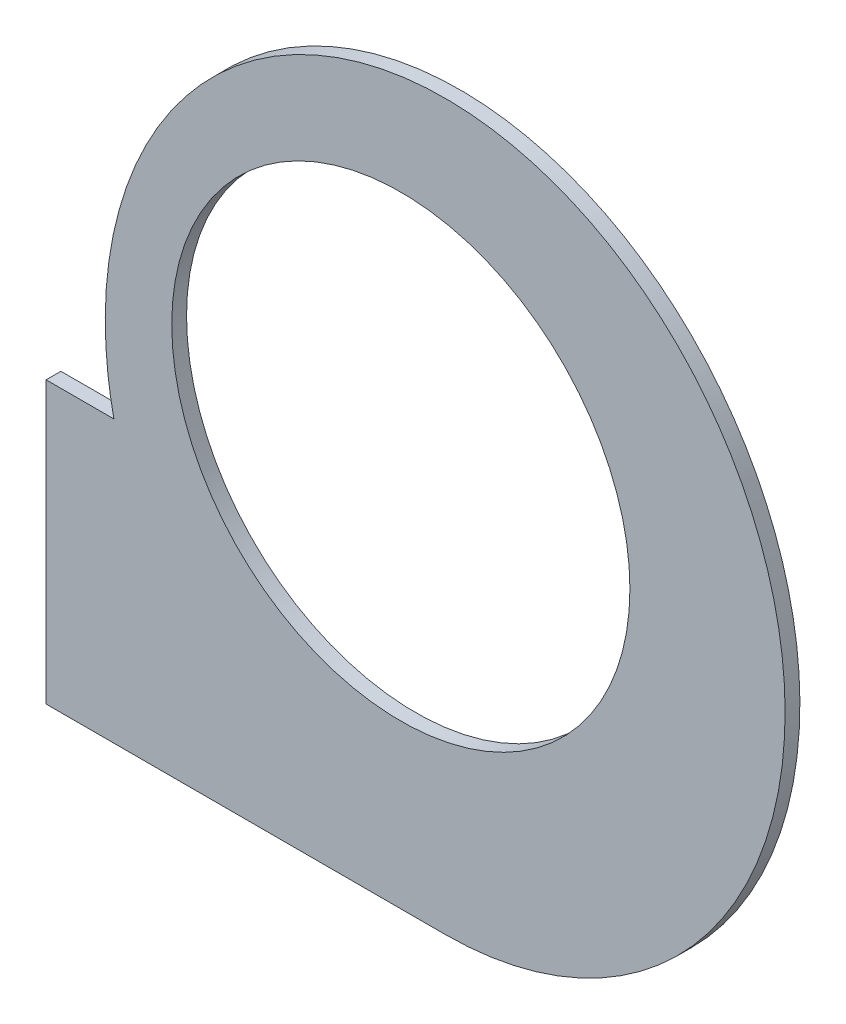
SolidWorks part; units mm, degrees
ref_plane "Plano frontal" through (0, 0, 0) normal (0, 0, 1) x (1, 0, 0)
ref_plane "Plano superior" through (0, 0, 0) normal (0, 1, 0) x (1, 0, 0)
ref_plane "Plano direito" through (0, 0, 0) normal (1, 0, 0) x (0, 0, -1)
sketch "Esboço1" plane through (0, 0, 0) normal (0, 0, 1) x (1, 0, 0)
  line L0 (0, -24.5) -> (-27, -24.5)
  line L1 (-27, -24.5) -> (-27, -5.5)
  line L2 (-27, -5.5) -> (-22.413, -5.5)
  circle A0 centre (-3, 2) radius 15.5
  ellipse E0 centre (0, 0) end of major axis (0, 24.5) minor radius 23 (0, -24.5) -> (-22.413, -5.5) ccw
  dimension "D1" = 49
  dimension "D5" = 22.5
  dimension "D7" = 31
  dimension "D2" = 46
  dimension "D3" = 50
  dimension "D4" = 19
  dimension "D6" = 20
extrude "Ressalto-extrusão1" add sketch "Esboço1" along normal blind 1
